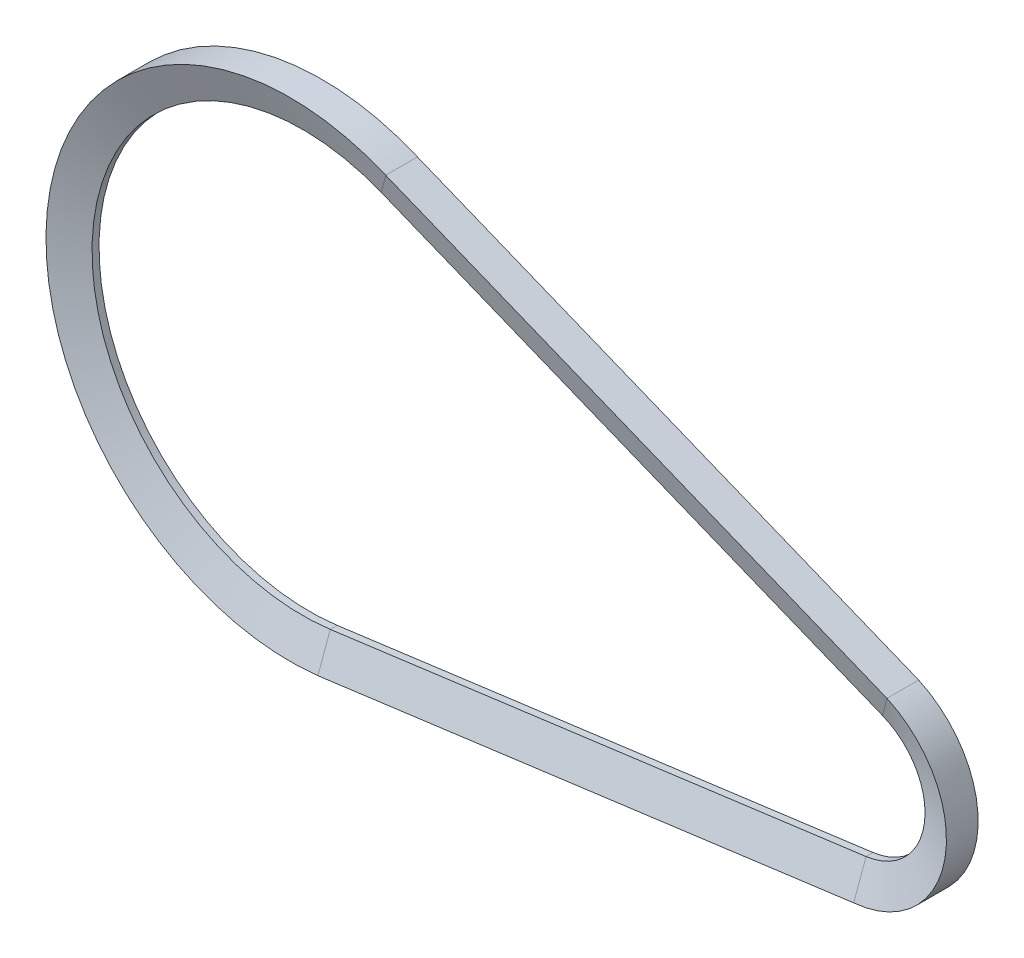
SolidWorks part; units mm, degrees
ref_plane "Front Plane" through (0, 0, 0) normal (0, 0, 1) x (1, 0, 0)
ref_plane "Top Plane" through (0, 0, 0) normal (0, 1, 0) x (1, 0, 0)
ref_plane "Right Plane" through (0, 0, 0) normal (1, 0, 0) x (0, 0, -1)
sketch "Sketch1" plane through (0, 0, 0) normal (0, 0, 1) x (1, 0, 0)
  line L0 (17.4127, 43.1167) -> (128.117, -1.5914)
  line L1 (6.1247, -46.0949) -> (124.4757, -30.3693)
  arc A0 (17.4127, 43.1167) -> (6.1247, -46.0949) centre (0, 0) ccw
  arc A1 (124.4757, -30.3693) -> (128.117, -1.5914) centre (122.5, -15.5) ccw
  dimension "D3" = 93
  dimension "D4" = 30
  dimension "D1" = 122.5
  dimension "D2" = 15.5
ref_plane "Plane1" through (6.1247, 0, 0) normal (-1, 0, 0) x (0, 0, 1)
sketch "Sketch2" plane through (6.1247, 0, 0) normal (-1, 0, 0) x (0, 0, 1)
  line L0 (0, -46.0949) -> (0, -35.9832) construction
  line L1 (0.7702, -46.0949) -> (-0.7702, -46.0949)
  line L2 (3.5, -53.5949) -> (-3.5, -53.5949)
  line L3 (-3.5, -53.5949) -> (-0.7702, -46.0949)
  line L4 (3.5, -53.5949) -> (0.7702, -46.0949)
  line L5 (0, -46.0949) -> (0, -348.4297) construction
  point P6 (0, -46.0949)
  point P9 (0, -53.5949)
  dimension "D1" = 7
  dimension "D2" = 7.5
  dimension "D3" = 40
  dimension "D4" = 0
sweep "Sweep1" add profiles "Sketch2" path "Sketch1"
